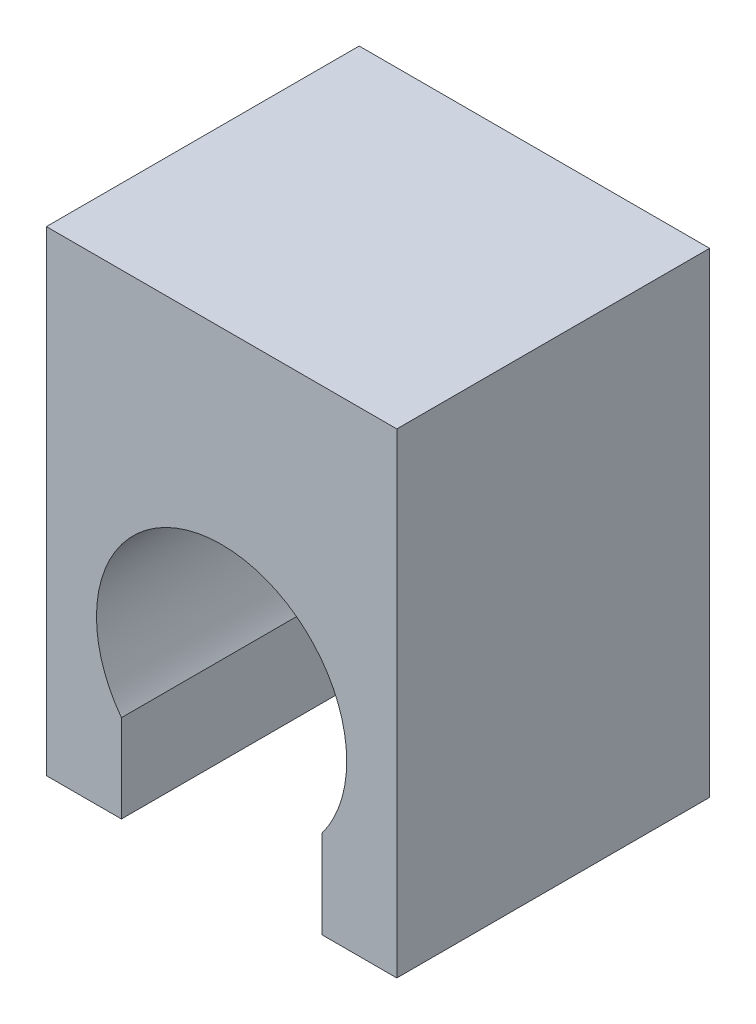
SolidWorks part; units mm, degrees
ref_plane "Front Plane" through (0, 0, 0) normal (0, 0, 1) x (1, 0, 0)
ref_plane "Top Plane" through (0, 0, 0) normal (0, 1, 0) x (1, 0, 0)
ref_plane "Right Plane" through (0, 0, 0) normal (1, 0, 0) x (0, 0, -1)
sketch "Sketch1" plane through (0, 0, 0) normal (0, 0, 1) x (1, 0, 0)
  line L0 (-4.0008, 2.1136) -> (-6.3997, 2.1136)
  line L2 (-6.3997, 13.3161) -> (4.8025, 13.3161)
  line L4 (4.8025, 2.1136) -> (2.4037, 2.1136)
  line L7 (-6.3997, 2.1136) -> (-6.3997, 13.3161)
  line L8 (-4.0008, 4.9191) -> (-4.0008, 2.1136)
  line L9 (2.4037, 4.9191) -> (2.4037, 2.1136)
  line L10 (4.8025, 2.1136) -> (4.8025, 13.3161)
  arc A0 (2.4037, 4.9191) -> (-4.0008, 4.9191) centre (-0.7986, 7.3161) ccw
  dimension "D2" = 6
extrude "Boss-Extrude1" add sketch "Sketch1" along normal blind 10 contours L2 L10 L4 L9 A0 L8 L0 L7
sketch "Sketch2" plane through (0, 13.3161, 0) normal (0, 1, 0) x (1, 0, 0)
  line L4 (4.8025, 0) -> (-6.3997, 0)
  line L5 (-6.3997, 0) -> (-6.3997, -10)
  line L6 (-6.3997, -10) -> (4.8025, -10)
  line L7 (4.8025, -10) -> (4.8025, 0)
  line L8 (4.8025, 0) -> (-6.3997, 0)
  line L9 (-6.3997, 0) -> (-6.3997, -10)
  line L10 (-6.3997, -10) -> (4.8025, -10)
  line L11 (4.8025, -10) -> (4.8025, 0)
  dimension "D1" = 0
extrude "Boss-Extrude2" add sketch "Sketch2" along normal blind 4
